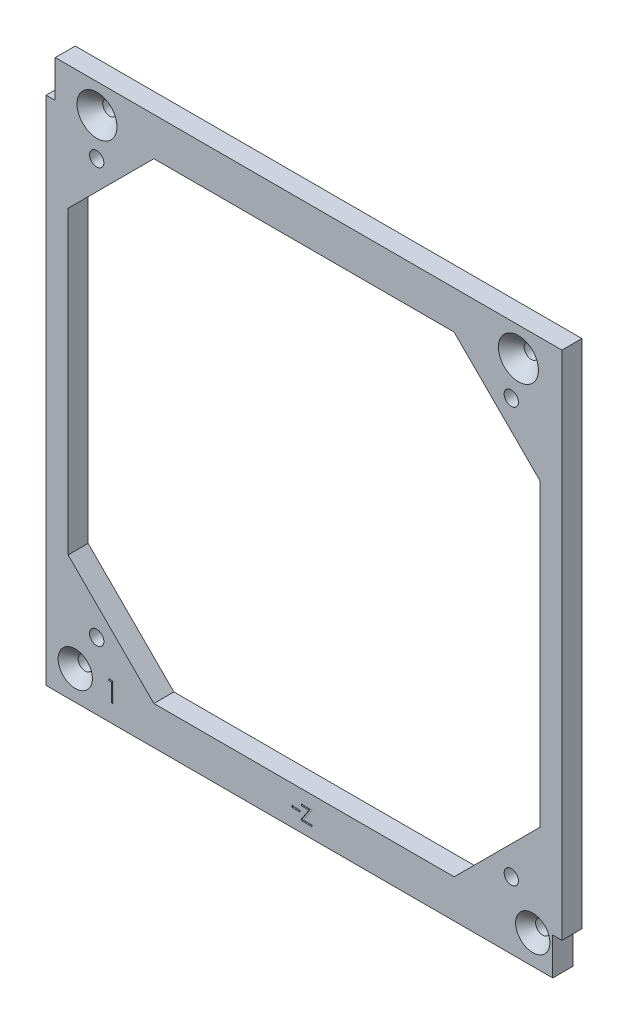
SolidWorks part; units mm, degrees
material "Liga 6061"
ref_plane "Plano frontal" through (0, 0, 0) normal (0, 0, 1) x (1, 0, 0)
ref_plane "Plano superior" through (0, 0, 0) normal (0, 1, 0) x (1, 0, 0)
ref_plane "Plano direito" through (0, 0, 0) normal (1, 0, 0) x (0, 0, -1)
sketch "Esboço1" plane through (0, 0, 0) normal (0, 0, 1) x (1, 0, 0)
  line L1 (-45.1, 47.95) -> (45.1, 47.95)
  line L2 (-45.1, 47.95) -> (-45.1, -47.95)
  line L3 (-45.1, -47.95) -> (45.1, -47.95)
  line L4 (45.1, 47.95) -> (45.1, -47.95)
  point P0 (0, 0)
  dimension "D1" = 90.2
  dimension "D2" = 95.9
sketch "Esboço2" plane through (0, 0, 0) normal (0, 0, 1) x (1, 0, 0)
  line L0 (-45.1, 47.95) -> (-45.1, -47.95) construction
  line L1 (-45.1, 47.95) -> (45.1, 47.95) construction
  line L5 (-45.1, -47.95) -> (45.1, -47.95) construction
  circle A0 centre (-36.2, 42.85) radius 1.25
  circle A1 centre (37.5, 42.85) radius 1.25
  circle A2 centre (40, -42.85) radius 1.25
  circle A3 centre (-40, -42.85) radius 1.25
  dimension "D2" = 82.6
  dimension "D3" = 5.1
  dimension "D1" = 8.9
  dimension "D4" = 85.1
  dimension "D5" = 5.1
  dimension "D6" = 5.1
sketch "Esboço3" plane through (0, 0, 0) normal (0, 0, 1) x (1, 0, 0)
  line L1 (0, -50) -> (0, 0) construction
  line L2 (-50, 50) -> (50, 50) construction
  line L3 (-50, 50) -> (-50, -50) construction
  line L4 (-50, -50) -> (50, -50) construction
  line L5 (50, 50) -> (50, -50) construction
  line L6 (0, 0) -> (50, 0) construction
  line L8 (-26.25, 41.25) -> (26.25, 41.25)
  line L9 (-41.25, 26.25) -> (-41.25, -26.25)
  line L10 (41.25, 26.25) -> (41.25, -26.25)
  line L11 (-26.25, -41.25) -> (26.25, -41.25)
  line L12 (-41.25, 50) -> (-41.25, -50) construction
  line L13 (-50, 41.25) -> (50, 41.25) construction
  line L14 (41.25, 50) -> (41.25, -50) construction
  line L15 (-50, -41.25) -> (50, -41.25) construction
  line L16 (-26.25, 41.25) -> (-41.25, 26.25)
  line L17 (26.25, 41.25) -> (41.25, 26.25)
  line L18 (41.25, -26.25) -> (26.25, -41.25)
  line L19 (-41.25, -26.25) -> (-26.25, -41.25)
  point P16 (-41.25, 41.25)
  point P17 (41.25, 41.25)
  point P18 (-41.25, -41.25)
  point P19 (41.25, -41.25)
  dimension "D1" = 100
  dimension "D2" = 100
  dimension "D3" = 8.75
  dimension "D4" = 8.75
  dimension "D5" = 8.75
  dimension "D6" = 8.75
extrude "Ressalto-extrusão1" add sketch "Esboço1" along normal blind 3.5
extrude "Corte-extrusão1" cut sketch "Esboço2" along normal blind 5
extrude "Corte-extrusão3" cut sketch "Esboço3" along normal blind 5
sketch "Esboço4" plane through (0, 0, 0) normal (0, 0, 1) x (1, 0, 0)
  line L3 (-36.25, 50) -> (-36.25, -50)
  line L4 (-36.25, 50) -> (-36.25, -50) construction
  line L6 (-50, 36.25) -> (50, 36.25)
  line L7 (-50, 36.25) -> (50, 36.25) construction
  line L9 (36.25, 50) -> (36.25, -50)
  line L10 (36.25, 50) -> (36.25, -50) construction
  line L12 (-50, -36.25) -> (50, -36.25)
  line L13 (-50, -36.25) -> (50, -36.25) construction
  circle A0 centre (-36.25, 36.25) radius 1.25
  circle A1 centre (36.25, 36.25) radius 1.25
  circle A2 centre (-36.25, -36.25) radius 1.25
  circle A3 centre (36.25, -36.25) radius 1.25
  dimension "D1" = 13.75
  dimension "D2" = 13.75
  dimension "D3" = 13.75
  dimension "D4" = 13.75
extrude "Corte-extrusão2" cut sketch "Esboço4" along normal blind 10
chamfer "Chanfro4" distance 1.75 angle 45 1 edges at (-38.75, -42.85, 3.5)
chamfer "Chanfro5" distance 1.75 angle 45 1 edges at (41.25, -42.85, 3.5)
chamfer "Chanfro6" distance 2.25 angle 45 1 edges at (-34.95, 42.85, 3.5)
chamfer "Chanfro7" distance 2.25 angle 45 1 edges at (38.75, 42.85, 3.5)
sketch "Esboço5" plane through (0, 0, 3.5) normal (0, 0, 1) x (1, 0, 0)
  text T0 "1"
extrude "Corte-extrusão4" cut sketch "Esboço5" against normal blind 0.2
sketch "Esboço6" plane through (0, 0, 0) normal (0, 0, -1) x (-1, 0, 0)
  text T0 "1"
extrude "Corte-extrusão5" cut sketch "Esboço6" against normal blind 0.2
sketch "Esboço7" plane through (0, 0, 0) normal (0, 0, -1) x (-1, 0, 0)
  line L0 (-43.5, -47.95) -> (-43.5, -41.45)
  line L1 (45.1, -47.95) -> (-45.1, -47.95) construction
  line L2 (-43.5, -41.45) -> (-45.1, -41.45)
  line L3 (-45.1, 47.95) -> (-45.1, -47.95) construction
  line L4 (-45.1, -41.45) -> (-45.1, -47.95)
  line L5 (-45.1, -47.95) -> (-43.5, -47.95)
extrude "Corte-extrusão7" cut sketch "Esboço7" against normal blind 5 and the other way through all
sketch "Esboço8" plane through (0, 0, 3.5) normal (0, 0, 1) x (1, 0, 0)
  line L0 (-43.5, 47.95) -> (-43.5, 41.45)
  line L1 (-45.1, 47.95) -> (45.1, 47.95) construction
  line L2 (-43.5, 41.45) -> (-45.1, 41.45)
  line L3 (-45.1, 47.95) -> (-45.1, -47.95) construction
  line L6 (-43.5, 47.95) -> (-43.5, 48.4109)
  line L7 (-43.5, 48.4109) -> (-45.2872, 48.4109)
  line L8 (-45.2872, 48.4109) -> (-45.2872, 41.45)
  line L9 (-45.1, 41.45) -> (-45.2872, 41.45)
extrude "Corte-extrusão8" cut sketch "Esboço8" against normal blind 5
sketch "Esboço9" plane through (0, 0, 3.5) normal (0, 0, 1) x (1, 0, 0)
  text T0 "-z"
extrude "Corte-extrusão9" cut sketch "Esboço9" against normal blind 0.2
